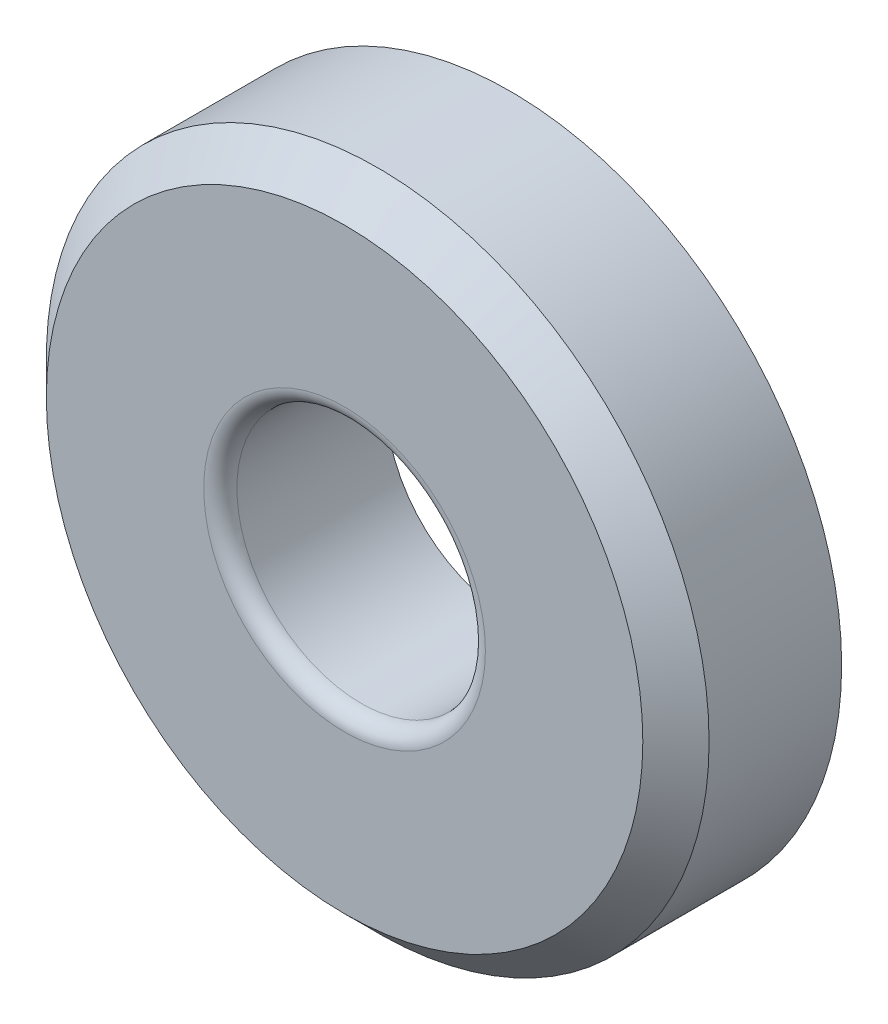
SolidWorks part; units mm, degrees
ref_plane "Front Plane" through (0, 0, 0) normal (0, 0, 1) x (1, 0, 0)
ref_plane "Top Plane" through (0, 0, 0) normal (0, 1, 0) x (1, 0, 0)
ref_plane "Right Plane" through (0, 0, 0) normal (1, 0, 0) x (0, 0, -1)
sketch "Sketch2" plane through (0, 0, 0) normal (0, 0, 1) x (1, 0, 0)
  circle A0 centre (0, 0) radius 25.4
  circle A1 centre (0, 0) radius 9.525
  dimension "D1" = 50.8
  dimension "D2" = 19.05
extrude "Boss-Extrude1" add sketch "Sketch2" along normal blind 12.7
chamfer "Chamfer1" distance 2.54 angle 45 1 edges at (25.4, 0, 12.7)
fillet "Fillet1" radius 1.27 1 edges at (9.525, 0, 12.7)
